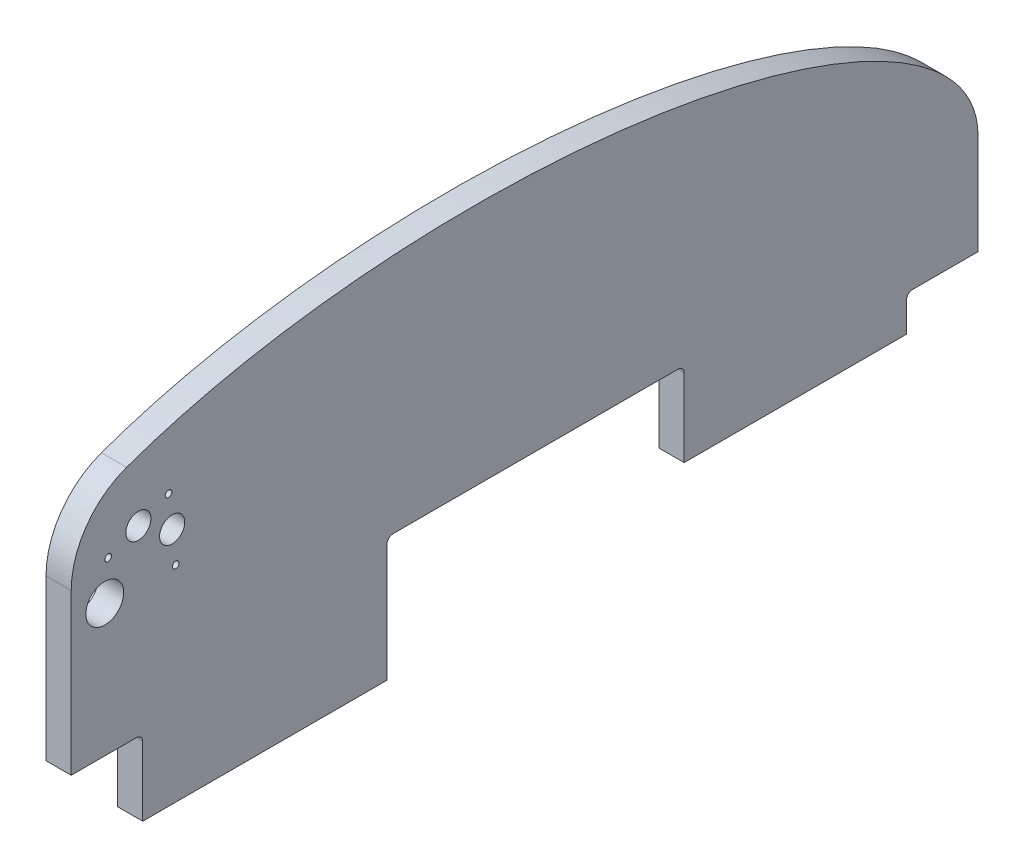
SolidWorks part; units mm, degrees
ref_plane "Front Plane" through (0, 0, 0) normal (0, 0, 1) x (1, 0, 0)
ref_plane "Top Plane" through (0, 0, 0) normal (0, 1, 0) x (1, 0, 0)
ref_plane "Right Plane" through (0, 0, 0) normal (1, 0, 0) x (0, 0, -1)
sketch "Sketch1" plane through (0, 0, 0) normal (1, 0, 0) x (0, 0, -1)
  line L0 (0, 0) -> (226.4213, 0) construction
  line L1 (0, 0) -> (0, 158.9703) construction
  line L2 (0, 133.35) -> (133.6465, 133.35) construction
  line L3 (54.102, 134.9375) -> (0, 134.9375)
  line L4 (54.102, 134.9375) -> (54.102, 77.7875)
  line L5 (54.102, 77.7875) -> (238.76, 77.7875)
  line L6 (0, 134.9375) -> (0, 255.9838)
  line L7 (0, 316.4238) -> (150.0045, 316.4238)
  line L8 (27.94, 263.4826) -> (73.66, 282.4479) construction
  line L9 (27.94, 263.4826) -> (41.3174, 295.8252) construction
  line L10 (41.3174, 295.8252) -> (73.66, 282.4479) construction
  line L11 (79.0859, 233.2487) -> (73.66, 282.4479) construction
  line L12 (238.76, 77.7875) -> (238.76, 171.45)
  line L13 (238.76, 171.45) -> (463.55, 171.45)
  line L14 (463.55, 171.45) -> (463.55, 107.95)
  line L15 (463.55, 107.95) -> (631.698, 107.95)
  line L16 (631.698, 107.95) -> (631.698, 134.9375)
  line L17 (631.698, 134.9375) -> (685.8, 134.9375)
  line L18 (685.8, 134.9375) -> (685.8, 211.1375)
  line L19 (251.8265, 355.6) -> (416.7294, 355.6) construction
  circle A0 centre (25.4, 234.95) radius 14.2875
  circle A1 centre (25.4, 234.95) radius 22.86 construction
  circle A2 centre (50.8, 272.9652) radius 22.86 construction
  circle A3 centre (50.8, 272.9652) radius 9.525
  circle A4 centre (73.66, 282.4479) radius 2.54
  circle A5 centre (27.94, 263.4826) radius 2.54
  circle A6 centre (25.4, 234.95) radius 15.24 construction
  circle A7 centre (76.373, 257.8483) radius 40.64 construction
  circle A8 centre (76.373, 257.8483) radius 9.525
  circle A9 centre (73.66, 282.4479) radius 2.54
  circle A10 centre (79.0859, 233.2487) radius 2.54
  arc A11 (41.9151, 315.7026) -> (0, 255.9838) centre (63.5, 255.9838) ccw
  ellipse E1 centre (304.8, 211.1375) end of major axis (685.8, 211.1375) minor radius 144.4625 (685.8, 211.1375) -> (41.9151, 315.7026) ccw
  dimension "D1" = 28.575
  dimension "D8" = 45.72
  dimension "D9" = 35
  dimension "D10" = 19.05
  dimension "D11" = 30.48
  dimension "D12" = 81.28
  dimension "D13" = 5.08
  dimension "D15" = 27.94
  dimension "D26" = 63.5
  dimension "D2" = 234.95
  dimension "D3" = 25.4
  dimension "D4" = 133.35
  dimension "D5" = 1.5875
  dimension "D6" = 57.15
  dimension "D7" = 54.102
  dimension "D14" = 50.8
  dimension "D16" = 316.4238
  dimension "D17" = 685.8
  dimension "D18" = 54.102
  dimension "D19" = 238.76
  dimension "D20" = 25.4
  dimension "D21" = 463.55
  dimension "D22" = 38.1
  dimension "D23" = 355.6
  dimension "D24" = 76.2
  dimension "D25" = 304.8
extrude "Boss-Extrude1" add sketch "Sketch1" along normal blind 19.05
fillet "Fillet1" radius 4.7625 4 edges at (9.525, 134.9375, -631.698) (9.525, 134.9375, -54.102) (9.525, 171.45, -463.55) (9.525, 171.45, -238.76)
